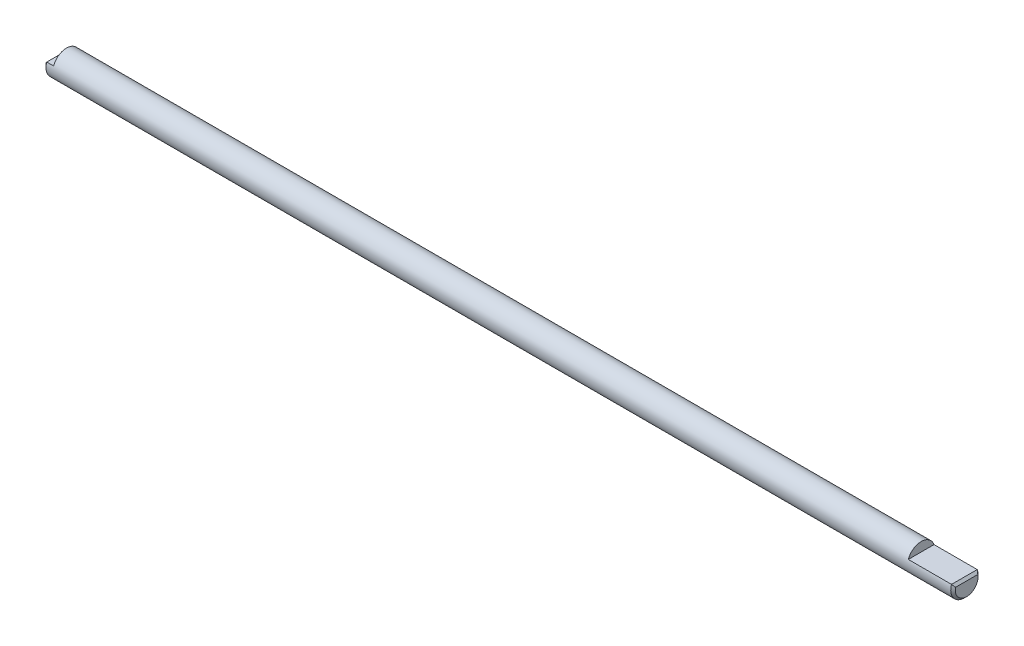
SolidWorks part; units mm, degrees
ref_plane "Front Plane" through (0, 0, 0) normal (0, 0, 1) x (1, 0, 0)
ref_plane "Top Plane" through (0, 0, 0) normal (0, 1, 0) x (1, 0, 0)
ref_plane "Right Plane" through (0, 0, 0) normal (1, 0, 0) x (0, 0, -1)
sketch "Sketch1" plane through (0, 0, 0) normal (0, 0, 1) x (1, 0, 0)
  line L0 (0, 0) -> (200, 0) construction
  line L2 (0, 0) -> (200, 0)
  line L3 (0, 0) -> (0, 3)
  line L4 (0, 3) -> (200, 3)
  line L5 (200, 0) -> (200, 3)
  dimension "D" = 6
  dimension "L" = 200
revolve "Revolve1" add sketch "Sketch1" angle 360 about L0
sketch "Sketch2" plane through (0, 0, 0) normal (0, 0, 1) x (1, 0, 0)
  line L0 (0, 3) -> (200, 3) construction
  line L1 (0, 3) -> (2, 3)
  line L2 (0, 3) -> (0, 1)
  line L3 (0, 1) -> (2, 1)
  line L4 (2, 3) -> (2, 1)
  line L5 (190, 3) -> (200, 3)
  line L6 (190, 3) -> (190, 1)
  line L7 (190, 1) -> (200, 1)
  line L8 (200, 3) -> (200, 1)
  line L9 (0, 0) -> (0, 3) construction
  line L10 (200, 0) -> (200, 3) construction
  line L11 (0, -3) -> (200, -3) construction
  dimension "W" = 4
  dimension "F" = 2
  dimension "T" = 10
  dimension "D" = 6
  dimension "W_R" = 4
extrude "Cut-Extrude1" cut sketch "Sketch2" against normal through all and the other way through all
chamfer "Chamfer1" distance 0.5 angle 45 4 edges at (0, -3, 0) (200, -3, 0) (0, 1, 0) (200, 1, 0)
sketch "Sketch3" [suppressed] plane through (0, 0, 0) normal (0, 0, 1) x (1, 0, 0)
  line L0 (0, 0.5) -> (0, -2.5) construction
  line L1 (4, 3) -> (6, 3)
  line L2 (4, 3) -> (4, 2)
  line L3 (4, 2) -> (6, 2)
  line L4 (6, 3) -> (6, 2)
  line L5 (5, 3) -> (5, 2) construction
  line L7 (0, 3) -> (24, 3) construction
  dimension "H" = 1
  dimension "G" = 2
  dimension "FC" = 4
extrude "Cut-Extrude2" [suppressed] cut sketch "Sketch3" against normal through all and the other way through all
ref_plane "FC_SEC" [suppressed] through (5, 0, 0) normal (1, 0, 0) x (0, 0, -1)
sketch "Sketch4" [suppressed] plane through (0, 0, 0) normal (0, 0, 1) x (1, 0, 0)
  line L0 (5, 3) -> (5, 2) construction
  line L1 (4, 3) -> (6, 3)
  line L2 (4, 3) -> (4, 2)
  line L3 (4, 2) -> (6, 2)
  line L4 (6, 3) -> (6, 2)
  line L5 (18, 3) -> (20, 3)
  line L6 (18, 3) -> (18, 2)
  line L7 (18, 2) -> (20, 2)
  line L8 (20, 3) -> (20, 2)
  line L9 (19, 3) -> (19, 2) construction
  line L10 (0, 3) -> (24, 3) construction
  line L12 (0, 0) -> (0, 3) construction
  line L13 (24, 0) -> (24, 3) construction
  dimension "J" = 2
  dimension "V" = 2
  dimension "H" = 1
  dimension "WFC" = 4
  dimension "W_1" = 4
  dimension "H_R" = 1
extrude "Cut-Extrude3" [suppressed] cut sketch "Sketch4" against normal through all and the other way through all
ref_plane "WFC_SEC1" [suppressed] through (5, 0, 0) normal (1, 0, 0) x (0, 0, -1)
ref_plane "WFC_SEC2" [suppressed] through (19, 0, 0) normal (1, 0, 0) x (0, 0, -1)
sketch "Sketch5" [suppressed] plane through (0, 0, 0) normal (0, 0, 1) x (1, 0, 0)
  line L0 (0, 3) -> (24, 3) construction
  line L1 (3, -2) -> (11, -2)
  line L2 (3, -2) -> (3, -3)
  line L3 (3, -3) -> (11, -3)
  line L4 (11, -2) -> (11, -3)
  line L5 (3, 3) -> (11, 3)
  line L6 (3, 3) -> (3, 2)
  line L7 (3, 2) -> (11, 2)
  line L8 (11, 3) -> (11, 2)
  line L9 (0, 0.5) -> (0, -2.5) construction
  line L10 (24, 0) -> (24, 3) construction
  line L11 (7, -3) -> (7, -2) construction
  line L13 (0, 0) -> (24, 0) construction
  dimension "W_2" = 4
  dimension "L2_s" = 8
  dimension "SC" = 3
extrude "Cut-Extrude4" [suppressed] cut sketch "Sketch5" along normal through all and the other way through all
ref_plane "SC_SEC" [suppressed] through (7, 0, 0) normal (1, 0, 0) x (0, 0, -1)
sketch "Sketch6" [suppressed] plane through (0, 0, 0) normal (0, 0, 1) x (1, 0, 0)
  line L0 (0, 0) -> (24, 0) construction
  line L1 (24, -2.5) -> (24, 0.5) construction
  line L2 (0, 3) -> (24, 3) construction
  line L3 (5.3, 3) -> (6, 3)
  line L4 (5.3, 3) -> (5.3, 2.5)
  line L5 (5.3, 2.5) -> (6, 2.5)
  line L6 (6, 3) -> (6, 2.5)
  line L7 (0, 0.5) -> (0, -2.5) construction
  dimension "D_s" = 5
  dimension "M_s" = 0.7
  dimension "TA" = 6
revolve "Cut-Revolve1" [suppressed] cut sketch "Sketch6" angle 360 about L0
sketch "Sketch7" [suppressed] plane through (0, 0, 0) normal (0, 0, 1) x (1, 0, 0)
  line L0 (0, 3) -> (24, 3) construction
  line L1 (18, 3) -> (18.7, 3)
  line L2 (18, 3) -> (18, 2.5)
  line L3 (18, 2.5) -> (18.7, 2.5)
  line L4 (18.7, 3) -> (18.7, 2.5)
  line L5 (0, 0) -> (24, 0) construction
  line L6 (24, -2.5) -> (24, 0.5) construction
  dimension "D_s" = 5
  dimension "TB" = 6
  dimension "M_s" = 0.7
revolve "Cut-Revolve2" [suppressed] cut sketch "Sketch7" angle 360 about L5
